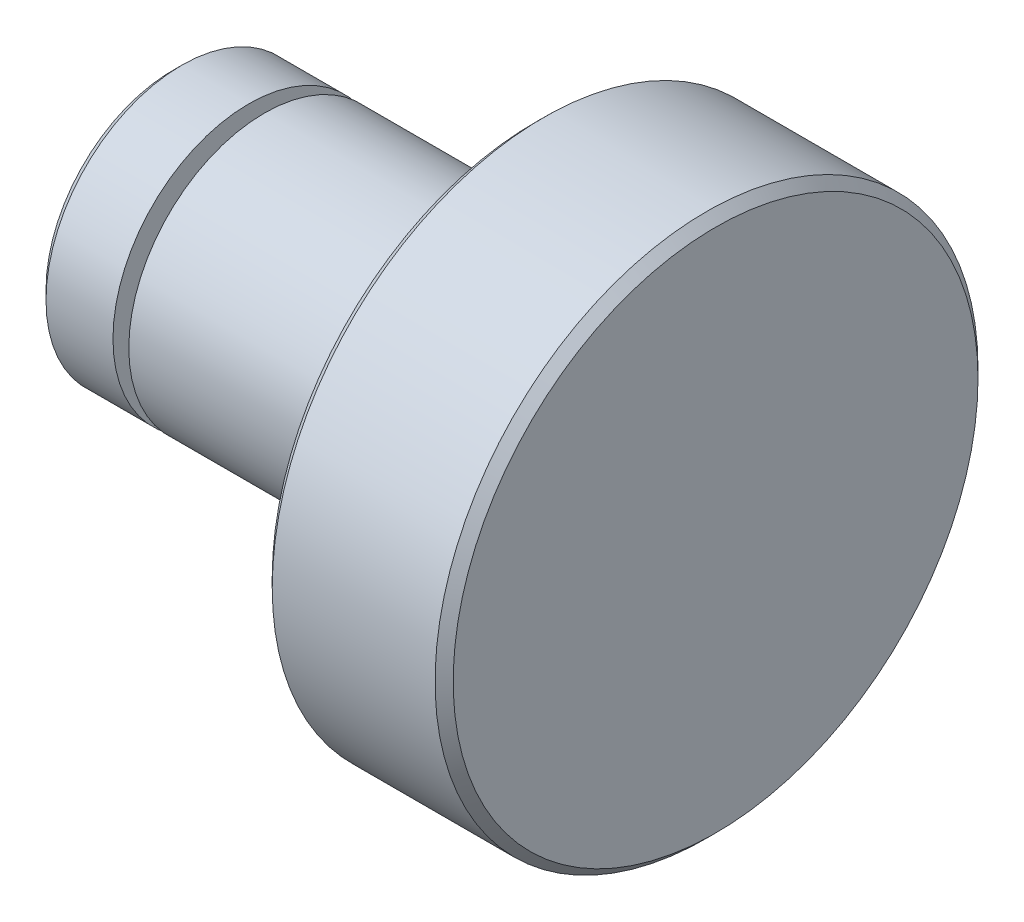
SolidWorks part; units mm, degrees
ref_plane "Piano frontale" through (0, 0, 0) normal (0, 0, 1) x (1, 0, 0)
ref_plane "Piano superiore" through (0, 0, 0) normal (0, 1, 0) x (1, 0, 0)
ref_plane "Piano destro" through (0, 0, 0) normal (1, 0, 0) x (0, 0, -1)
sketch "Schizzo1" plane through (0, 0, 0) normal (0, 0, 1) x (1, 0, 0)
  line L0 (0, 0) -> (-200.6705, 0) construction
  line L1 (0, 0) -> (0, 30)
  line L2 (0, 30) -> (-20, 30)
  line L3 (-20, 30) -> (-20, 15)
  line L4 (-20, 15) -> (-60, 15)
  line L5 (-60, 15) -> (-60, 0)
  line L6 (-60, 0) -> (0, 0)
  point P7 (-200.6705, 0)
  dimension "D1" = 15
  dimension "D2" = 30
  dimension "D3" = 20
  dimension "D4" = 40
revolve "Rivoluzione1" add sketch "Schizzo1" angle 360 about L0
chamfer "Smusso1" distance 1 angle 45 3 edges at (-20, 0, -30) (-60, 0, -15) (0, 0, -30)
sketch "Schizzo2" plane through (0, 0, 0) normal (0, 0, 1) x (1, 0, 0)
  line L1 (-50, 15) -> (-51.6, 15)
  line L2 (-50, 15) -> (-50, 12)
  line L3 (-50, 12) -> (-51.6, 12)
  line L4 (-51.6, 15) -> (-51.6, 12)
  line L5 (-20, 15) -> (-59, 15) construction
  line L6 (0, 0) -> (-68.5482, 0) construction
  line L7 (-50, 12) -> (-49.85, 12)
  line L8 (-49.85, 12) -> (-49.85, 15)
  line L9 (-49.85, 15) -> (-50, 15)
  point P13 (0, 0)
  dimension "D1" = 3
  dimension "D2" = 1.6
  dimension "D3" = 1.75
  dimension "D4" = 30
revolve "Taglia-Rivoluzione1" cut sketch "Schizzo2" angle 360 about L6
